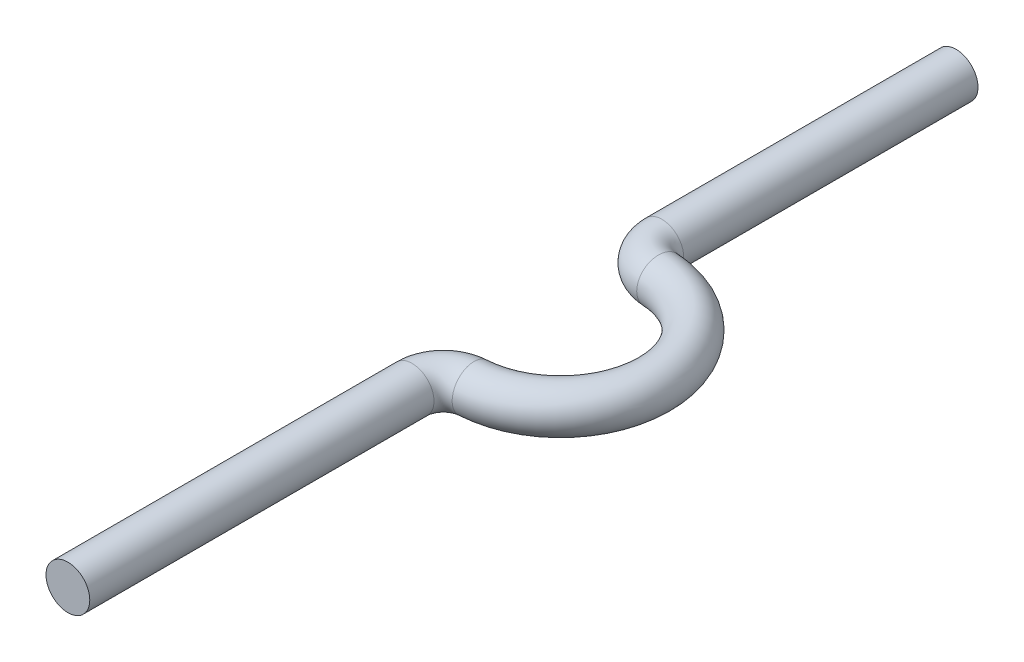
SolidWorks part; units mm, degrees
ref_plane "Alzado" through (0, 0, 0) normal (0, 0, 1) x (1, 0, 0)
ref_plane "Planta" through (0, 0, 0) normal (0, 1, 0) x (1, 0, 0)
ref_plane "Vista lateral" through (0, 0, 0) normal (1, 0, 0) x (0, 0, -1)
sketch "Croquis1" plane through (0, 0, 0) normal (0, 1, 0) x (1, 0, 0)
  line L0 (0, 0) -> (0, 55.0313)
  line L1 (0, 94.9531) -> (0, 142)
  arc A0 (4.6875, 60.0215) -> (4.6875, 89.9629) centre (3.75, 74.9922) ccw
  arc A1 (4.6875, 60.0215) -> (0, 55.0313) centre (5, 55.0313) ccw
  arc A2 (4.6875, 89.9629) -> (0, 94.9531) centre (5, 94.9531) cw
  point P11 (0, 89.5159)
  dimension "D1" = 142
  dimension "D2" = 30
  dimension "D3" = 5
sketch "Croquis2" plane through (0, 0, 0) normal (0, 0, 1) x (1, 0, 0)
  circle A0 centre (0, 0) radius 3.5
  dimension "D1" = 7
sweep "Barrer2" add profiles "Croquis2" path "Croquis1"
